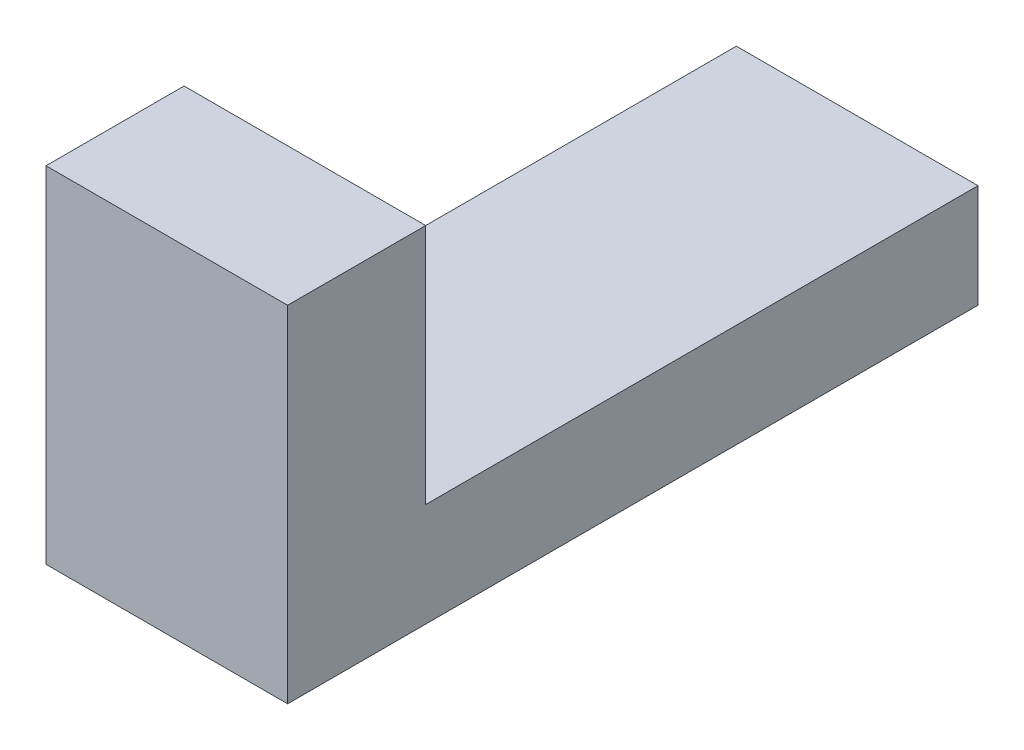
SolidWorks part; units mm, degrees
ref_plane "前视基准面" through (0, 0, 0) normal (0, 0, 1) x (1, 0, 0)
ref_plane "上视基准面" through (0, 0, 0) normal (0, 1, 0) x (1, 0, 0)
ref_plane "右视基准面" through (0, 0, 0) normal (1, 0, 0) x (0, 0, -1)
other "Configuration Table"
sketch "草图1" plane through (0, 0, 0) normal (0, 0, 1) x (1, 0, 0)
  line L1 (0, 0) -> (7, 0)
  line L2 (0, 0) -> (0, 3)
  line L3 (0, 3) -> (7, 3)
  line L4 (7, 0) -> (7, 3)
  dimension "D1" = 3
  dimension "D2" = 7
extrude "凸台-拉伸1" add sketch "草图1" along normal blind 20
sketch "草图2" plane through (0, 3, 0) normal (0, 1, 0) x (1, 0, 0)
  line L0 (7, -20) -> (7, 0) construction
  line L1 (0, -20) -> (7, -20)
  line L2 (0, -20) -> (0, -16)
  line L3 (0, -16) -> (7, -16)
  line L4 (7, -20) -> (7, -16)
  dimension "D1" = 4
extrude "凸台-拉伸2" add sketch "草图2" along normal blind 7
